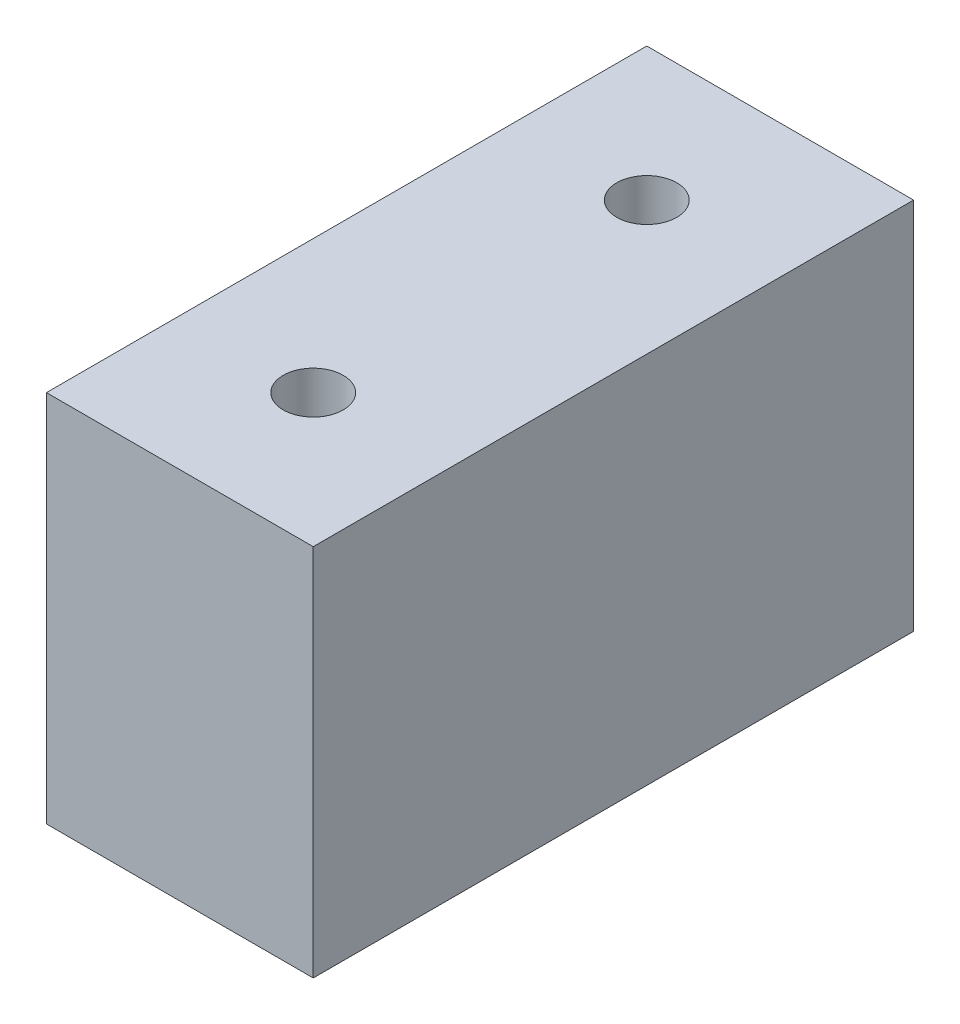
SolidWorks part; units mm, degrees
ref_plane "前视基准面" through (0, 0, 0) normal (0, 0, 1) x (1, 0, 0)
ref_plane "上视基准面" through (0, 0, 0) normal (0, 1, 0) x (1, 0, 0)
ref_plane "右视基准面" through (0, 0, 0) normal (1, 0, 0) x (0, 0, -1)
sketch "草图1" plane through (0, 0, 0) normal (0, 1, 0) x (1, 0, 0)
  line L0 (0, 22.5) -> (20, 22.5) construction
  line L1 (0, 0) -> (20, 0)
  line L2 (0, 0) -> (0, 45)
  line L3 (0, 45) -> (20, 45)
  line L4 (20, 0) -> (20, 45)
  line L5 (10, 22.5) -> (10, 35) construction
  circle A0 centre (10, 35) radius 2.25
  circle A1 centre (10, 10) radius 2.25
  dimension "D1" = 4.5
  dimension "D2" = 25
  dimension "D3" = 45
  dimension "D4" = 20
extrude "凸台-拉伸1" add sketch "草图1" along normal blind 28
